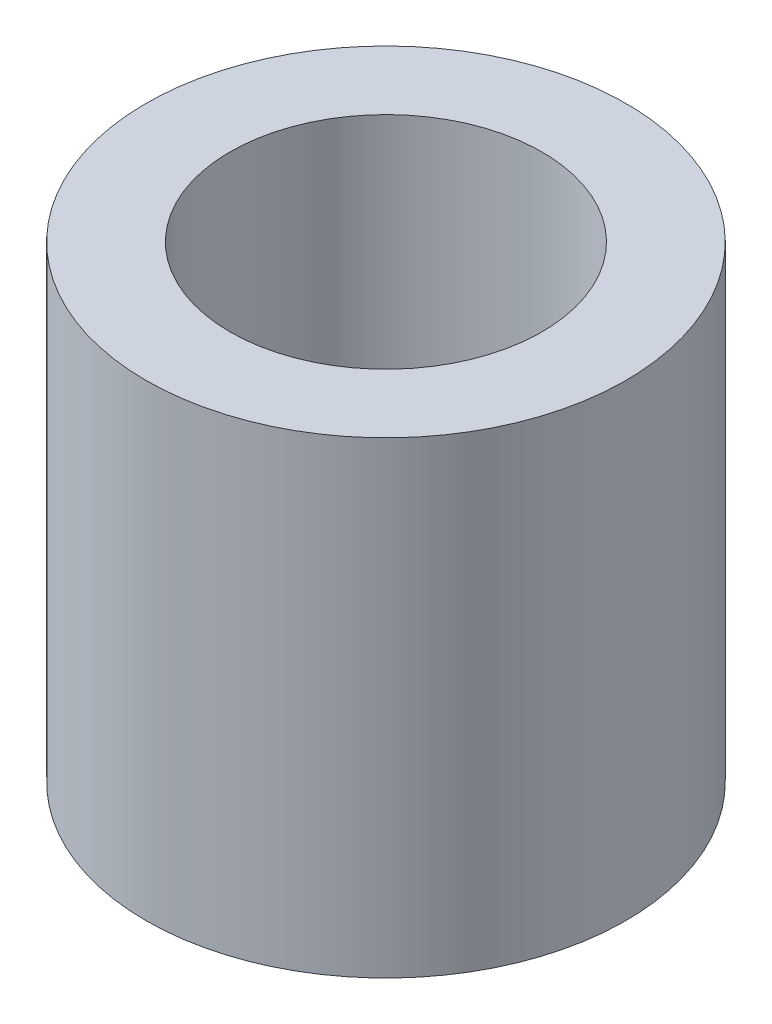
SolidWorks part; units mm, degrees
ref_plane "Front Plane" through (0, 0, 0) normal (0, 0, 1) x (1, 0, 0)
ref_plane "Top Plane" through (0, 0, 0) normal (0, 1, 0) x (1, 0, 0)
ref_plane "Right Plane" through (0, 0, 0) normal (1, 0, 0) x (0, 0, -1)
sketch "Sketch1" plane through (0, 0, 0) normal (0, 1, 0) x (1, 0, 0)
  circle A0 centre (0, 0) radius 4
  circle A1 centre (0, 0) radius 2.6
extrude "Boss-Extrude1" add sketch "Sketch1" along normal blind 7.8
